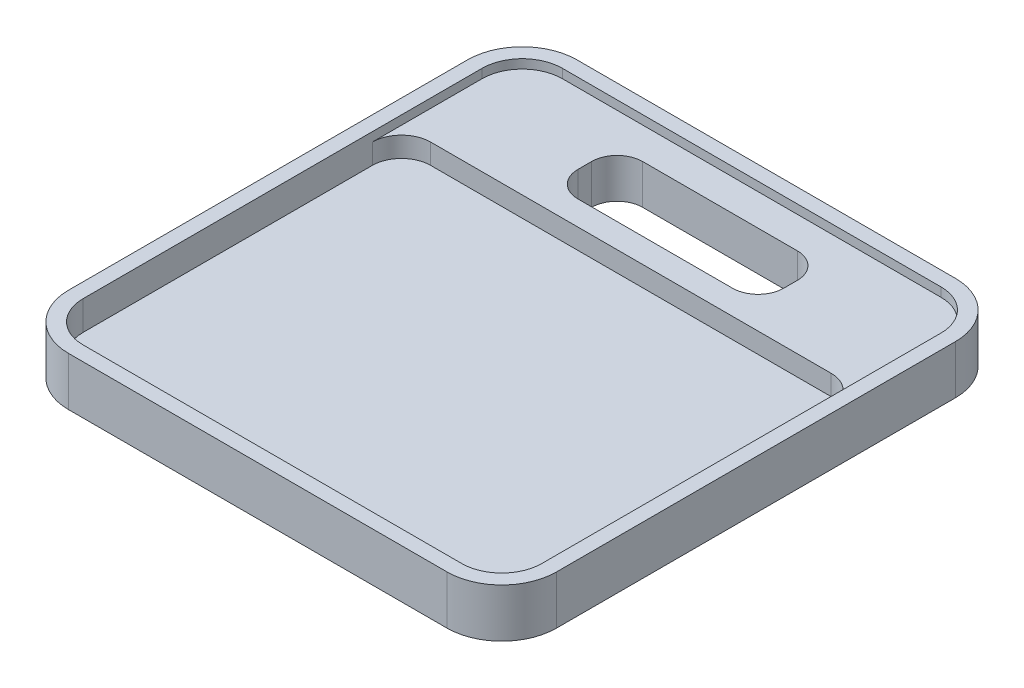
SolidWorks part; units mm, degrees
ref_plane "Front" through (0, 0, 0) normal (0, 0, 1) x (1, 0, 0)
ref_plane "Top" through (0, 0, 0) normal (0, 1, 0) x (1, 0, 0)
ref_plane "Right" through (0, 0, 0) normal (1, 0, 0) x (0, 0, -1)
sketch "草图1" plane through (0, 0, 0) normal (0, 1, 0) x (-1, 0, 0)
  line L4 (7.77, 10.5376) -> (-7.77, 10.5376) construction
  line L5 (-10.1176, 8.19) -> (-10.1176, -8.19) construction
  line L6 (-7.77, -10.5376) -> (7.77, -10.5376) construction
  line L7 (10.1176, -8.19) -> (10.1176, 8.19) construction
  line L8 (7.77, 10.4376) -> (-7.77, 10.4376)
  line L9 (-10.0176, 8.19) -> (-10.0176, -8.19)
  line L10 (-7.77, -10.4376) -> (7.77, -10.4376)
  line L11 (10.0176, -8.19) -> (10.0176, 8.19)
  line L12 (10.0176, 0) -> (-10.0176, 0) construction
  line L13 (0, -10.4376) -> (0, 0) construction
  line L14 (0, 0) -> (0, 10.4376) construction
  arc A4 (10.1176, 8.19) -> (7.77, 10.5376) centre (7.77, 8.19) ccw construction
  arc A5 (-7.77, 10.5376) -> (-10.1176, 8.19) centre (-7.77, 8.19) ccw construction
  arc A6 (-10.1176, -8.19) -> (-7.77, -10.5376) centre (-7.77, -8.19) ccw construction
  arc A7 (7.77, -10.5376) -> (10.1176, -8.19) centre (7.77, -8.19) ccw construction
  arc A8 (10.0176, 8.19) -> (7.77, 10.4376) centre (7.77, 8.19) ccw
  arc A9 (-7.77, 10.4376) -> (-10.0176, 8.19) centre (-7.77, 8.19) ccw
  arc A10 (-10.0176, -8.19) -> (-7.77, -10.4376) centre (-7.77, -8.19) ccw
  arc A11 (7.77, -10.4376) -> (10.0176, -8.19) centre (7.77, -8.19) ccw
  dimension "D1" = 0.1
extrude "凸台-拉伸1" add sketch "草图1" along normal blind 2
sketch "草图3" plane through (0, 2, 0) normal (0, 1, 0) x (1, 0, 0)
  line L12 (3.175, 8.9408) -> (-3.175, 8.9408)
  line L13 (4.625, 6.9308) -> (4.625, 7.4908)
  line L14 (-3.175, 5.4808) -> (3.175, 5.4808)
  line L15 (-4.625, 7.4908) -> (-4.625, 6.9308)
  line L20 (3.175, 8.9408) -> (-3.175, 8.9408)
  line L21 (4.625, 6.9308) -> (4.625, 7.4908)
  line L22 (-3.175, 5.4808) -> (3.175, 5.4808)
  line L23 (-4.625, 7.4908) -> (-4.625, 6.9308)
  arc A8 (4.625, 7.4908) -> (3.175, 8.9408) centre (3.175, 7.4908) ccw
  arc A9 (3.175, 5.4808) -> (4.625, 6.9308) centre (3.175, 6.9308) ccw
  arc A10 (-4.625, 6.9308) -> (-3.175, 5.4808) centre (-3.175, 6.9308) ccw
  arc A11 (-3.175, 8.9408) -> (-4.625, 7.4908) centre (-3.175, 7.4908) ccw
  arc A16 (4.625, 7.4908) -> (3.175, 8.9408) centre (3.175, 7.4908) ccw
  arc A17 (3.175, 5.4808) -> (4.625, 6.9308) centre (3.175, 6.9308) ccw
  arc A18 (-4.625, 6.9308) -> (-3.175, 5.4808) centre (-3.175, 6.9308) ccw
  arc A19 (-3.175, 8.9408) -> (-4.625, 7.4908) centre (-3.175, 7.4908) ccw
  dimension "D1" = 0.15
extrude "切除-拉伸1" cut sketch "草图3" against normal through all
sketch "草图4" plane through (0, 0, 0) normal (0, -1, 0) x (1, 0, 0)
  line L0 (-4.625, -7.4908) -> (-4.625, -6.9308) construction
  line L1 (-3.175, -5.4808) -> (3.175, -5.4808) construction
  line L2 (4.625, -6.9308) -> (4.625, -7.4908) construction
  line L3 (3.175, -8.9408) -> (-3.175, -8.9408) construction
  line L4 (-4.625, -7.4908) -> (-4.625, -6.9308)
  line L5 (-3.175, -5.4808) -> (3.175, -5.4808)
  line L6 (4.625, -6.9308) -> (4.625, -7.4908)
  line L7 (3.175, -8.9408) -> (-3.175, -8.9408)
  line L16 (3.175, -8.5408) -> (-3.175, -8.5408)
  line L17 (4.225, -6.9308) -> (4.225, -7.4908)
  line L18 (-3.175, -5.8808) -> (3.175, -5.8808)
  line L19 (-4.225, -7.4908) -> (-4.225, -6.9308)
  arc A0 (-4.625, -7.4908) -> (-3.175, -8.9408) centre (-3.175, -7.4908) ccw construction
  arc A1 (-3.175, -5.4808) -> (-4.625, -6.9308) centre (-3.175, -6.9308) ccw construction
  arc A2 (4.625, -6.9308) -> (3.175, -5.4808) centre (3.175, -6.9308) ccw construction
  arc A3 (3.175, -8.9408) -> (4.625, -7.4908) centre (3.175, -7.4908) ccw construction
  arc A4 (-4.625, -7.4908) -> (-3.175, -8.9408) centre (-3.175, -7.4908) ccw
  arc A5 (-3.175, -5.4808) -> (-4.625, -6.9308) centre (-3.175, -6.9308) ccw
  arc A6 (4.625, -6.9308) -> (3.175, -5.4808) centre (3.175, -6.9308) ccw
  arc A7 (3.175, -8.9408) -> (4.625, -7.4908) centre (3.175, -7.4908) ccw
  arc A16 (-4.225, -7.4908) -> (-3.175, -8.5408) centre (-3.175, -7.4908) ccw
  arc A17 (3.175, -8.5408) -> (4.225, -7.4908) centre (3.175, -7.4908) ccw
  arc A18 (4.225, -6.9308) -> (3.175, -5.8808) centre (3.175, -6.9308) ccw
  arc A19 (-3.175, -5.8808) -> (-4.225, -6.9308) centre (-3.175, -6.9308) ccw
  dimension "D1" = 0.4
extrude "凸台-拉伸2" add sketch "草图4" against normal offset from surface (1.63 mm away) 0.1 contours A4 L7 A7 L6 A6 L5 A5 L4
sketch "草图5" plane through (0, 2, 0) normal (0, 1, 0) x (1, 0, 0)
  line L0 (9.4176, 4.8808) -> (-9.4176, 4.8808)
  line L3 (3.175, 5.8808) -> (-3.175, 5.8808) construction
  line L8 (-7.77, -9.8376) -> (7.77, -9.8376)
  line L9 (9.4176, -8.19) -> (9.4176, 8.19)
  line L10 (7.77, 9.8376) -> (-7.77, 9.8376)
  line L11 (-9.4176, 8.19) -> (-9.4176, -8.19)
  line L12 (-7.77, -9.8376) -> (7.77, -9.8376)
  line L13 (9.4176, -8.19) -> (9.4176, 4.8808)
  line L15 (-9.4176, 4.8808) -> (-9.4176, -8.19)
  arc A8 (-9.4176, -8.19) -> (-7.77, -9.8376) centre (-7.77, -8.19) ccw
  arc A9 (7.77, -9.8376) -> (9.4176, -8.19) centre (7.77, -8.19) ccw
  arc A10 (9.4176, 8.19) -> (7.77, 9.8376) centre (7.77, 8.19) ccw
  arc A11 (-7.77, 9.8376) -> (-9.4176, 8.19) centre (-7.77, 8.19) ccw
  arc A12 (-9.4176, -8.19) -> (-7.77, -9.8376) centre (-7.77, -8.19) ccw
  arc A13 (7.77, -9.8376) -> (9.4176, -8.19) centre (7.77, -8.19) ccw
  dimension "D2" = 1
  dimension "D1" = 0.6
extrude "切除-拉伸2" cut sketch "草图5" against normal blind 1.2
sketch "草图7" plane through (0, 2, 0) normal (0, 1, 0) x (1, 0, 0)
  line L1 (9.4176, 8.19) -> (9.4176, 4.8808)
  line L2 (7.77, 9.8376) -> (-7.77, 9.8376)
  line L3 (7.77, 9.8376) -> (-7.77, 9.8376)
  line L4 (9.4176, 4.8808) -> (-9.4176, 4.8808)
  line L5 (9.4176, 4.8808) -> (-9.4176, 4.8808) construction
  line L6 (-9.4176, 4.8808) -> (-9.4176, -8.19) construction
  line L7 (-9.4176, 4.8808) -> (-9.4176, 8.19)
  arc A4 (-7.77, 9.8376) -> (-9.4176, 8.19) centre (-7.77, 8.19) ccw
  arc A5 (9.4176, 8.19) -> (7.77, 9.8376) centre (7.77, 8.19) ccw
  arc A6 (-7.77, 9.8376) -> (-9.4176, 8.19) centre (-7.77, 8.19) ccw
  arc A7 (9.4176, 8.19) -> (7.77, 9.8376) centre (7.77, 8.19) ccw
  dimension "D1" = 0.6
extrude "切除-拉伸3" cut sketch "草图7" against normal up to surface (0.37 mm away) up to face at (0, 1.63, -7.2108)
fillet "圆角3" radius 1.2 2 edges at (9.4176, 1.215, -4.8808) (-9.4176, 1.215, -4.8808)
fillet "圆角1" [suppressed] radius 1.2
